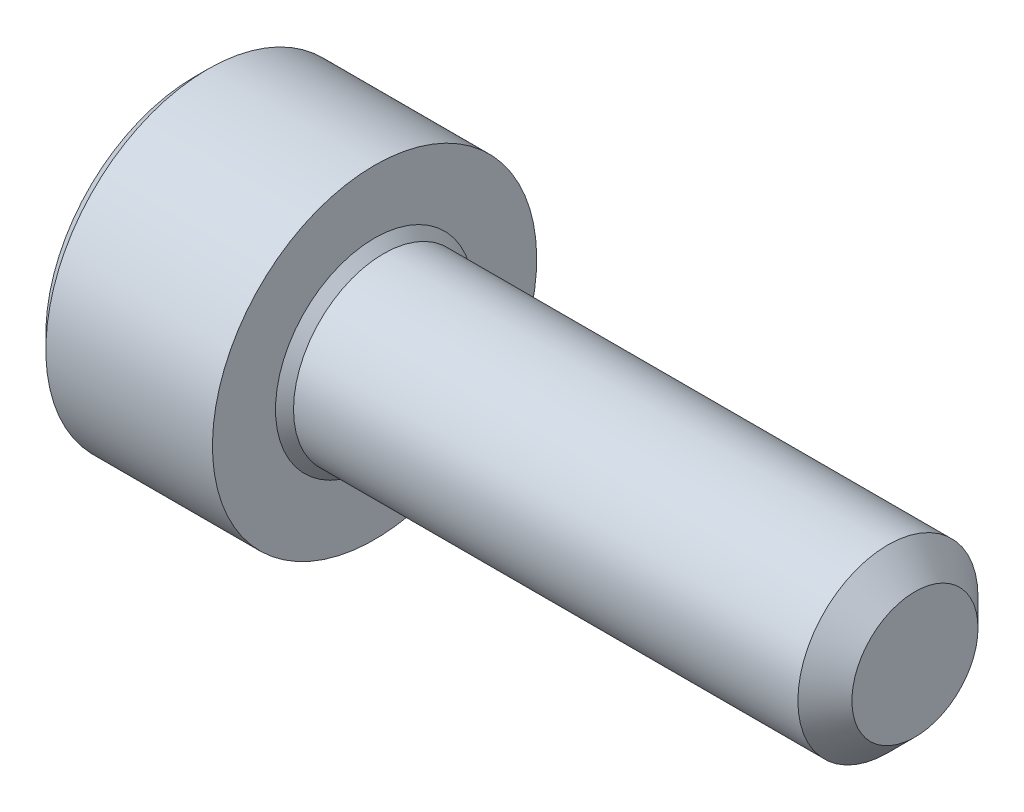
SolidWorks part; units mm, degrees
material "Galvanized Steel"
ref_plane "Front Plane" through (0, 0, 0) normal (0, 0, 1) x (1, 0, 0)
ref_plane "Top Plane" through (0, 0, 0) normal (0, 1, 0) x (1, 0, 0)
ref_plane "Right Plane" through (0, 0, 0) normal (1, 0, 0) x (0, 0, -1)
sketch "Sketch2" plane through (0, 0, 0) normal (1, 0, 0) x (0, 0, -1)
  circle A0 centre (0, 0) radius 1
  dimension "D1" = 2
extrude "Boss-Extrude1" add sketch "Sketch2" against normal blind 6
chamfer "Chamfer1" distance 0.3 angle 45 1 edges at (0, 0, -1)
sketch "Sketch6" plane through (0, 0, 0) normal (0, 0, 1) x (1, 0, 0)
  line L0 (-8, 0) -> (-8, 1.8)
  line L1 (-8, 0) -> (-6, 0)
  line L2 (-8, 1.8) -> (-6, 1.8)
  line L6 (-6, 1.8) -> (-6, 0)
  line L8 (-6, 0) -> (-14.6471, 0) construction
  line L10 (-6, 1) -> (-6, -1) construction
  dimension "D1" = 2
  dimension "D2" = 3.6
revolve "Revolve1" add sketch "Sketch6" angle 360 about L8
sketch "Sketch7" plane through (-8, 0, 0) normal (-1, 0, 0) x (0, 0, 1)
  line L1 (0, 0.8949) -> (-0.775, 0.4474)
  line L2 (-0.775, 0.4474) -> (-0.775, -0.4474)
  line L3 (-0.775, -0.4474) -> (0, -0.8949)
  line L4 (0, -0.8949) -> (0.775, -0.4474)
  line L5 (0.775, -0.4474) -> (0.775, 0.4474)
  line L6 (0.775, 0.4474) -> (0, 0.8949)
  circle A0 centre (0, 0) radius 0.775 construction
  dimension "D1" = 1.55
extrude "Cut-Extrude1" cut sketch "Sketch7" against normal blind 1
sketch "Sketch8" plane through (-8, 0, 0) normal (-1, 0, 0) x (0, 0, 1)
  circle A0 centre (0, 0) radius 0.9449
  dimension "D1" = 0.05
extrude "Cut-Extrude2" cut sketch "Sketch8" against normal blind 1 draft 45
chamfer "Chamfer2" distance 0.15 angle 45 1 edges at (-8, 1.8, 0)
chamfer "Chamfer3" distance 0.1 angle 45 1 edges at (-6, 1, 0)
